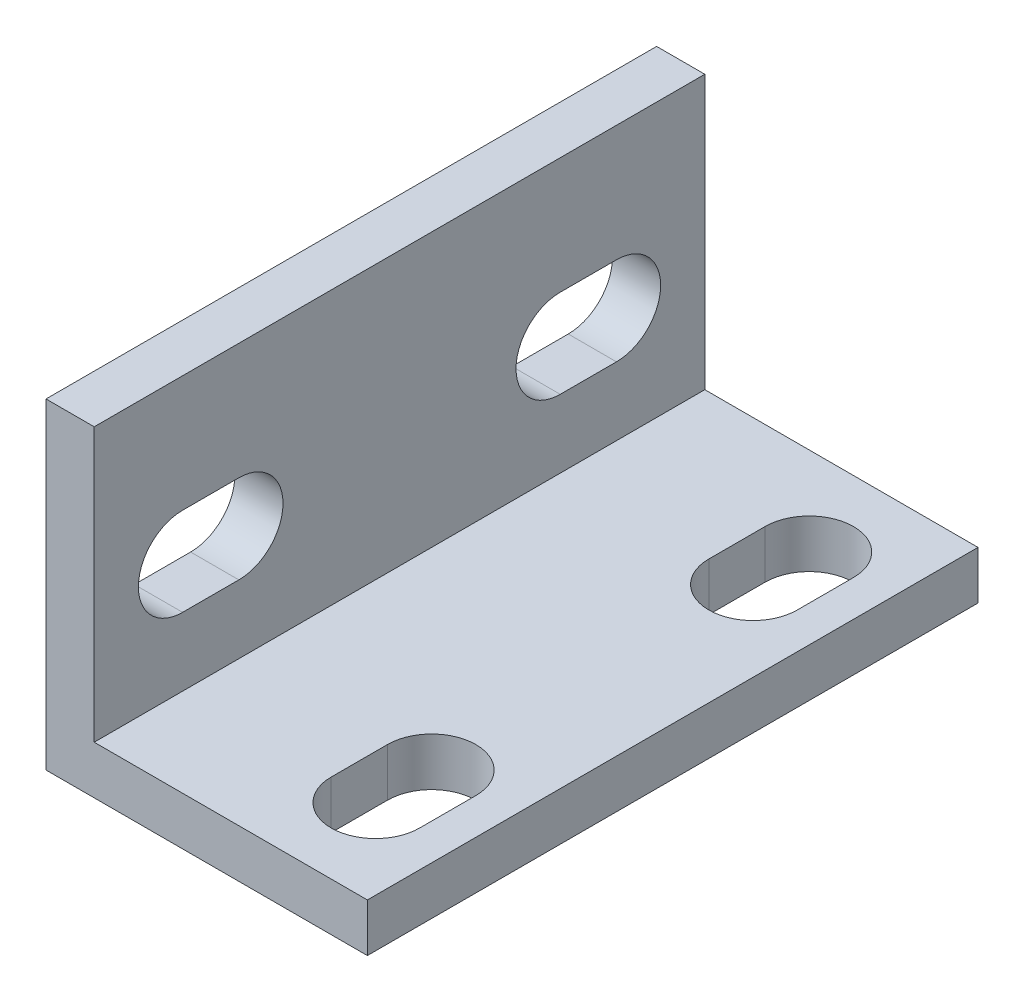
SolidWorks part; units mm, degrees
material "6061-T6 (SS)"
ref_plane "Front Plane" through (0, 0, 0) normal (0, 0, 1) x (1, 0, 0)
ref_plane "Top Plane" through (0, 0, 0) normal (0, 1, 0) x (1, 0, 0)
ref_plane "Right Plane" through (0, 0, 0) normal (1, 0, 0) x (0, 0, -1)
sketch "Sketch1" plane through (0, 0, 0) normal (0, 1, 0) x (1, 0, 0)
  line L1 (-10, 19) -> (10, 19)
  line L2 (-10, 19) -> (-10, -19)
  line L3 (-10, -19) -> (10, -19)
  line L4 (10, 19) -> (10, -19)
  line L5 (-10, 19) -> (10, -19) construction
  line L6 (-10, -19) -> (10, 19) construction
  point P0 (0, 0)
  dimension "D1" = 20
  dimension "D2" = 38
extrude "Boss-Extrude1" add sketch "Sketch1" along normal blind 20
sketch "Sketch2" plane through (0, 0, 19) normal (0, 0, 1) x (1, 0, 0)
  line L1 (10, 20) -> (-7, 20)
  line L2 (10, 20) -> (10, 3)
  line L3 (10, 3) -> (-7, 3)
  line L4 (-7, 20) -> (-7, 3)
  dimension "D1" = 17
  dimension "D2" = 17
extrude "Cut-Extrude1" cut sketch "Sketch2" against normal through all
sketch "Sketch3" plane through (0, 3, 0) normal (0, 1, 0) x (1, 0, 0)
  line L0 (5, -10) -> (5, -13.5) construction
  line L1 (7.75, -10) -> (7.75, -13.5)
  line L2 (2.25, -10) -> (2.25, -13.5)
  line L3 (10, 19) -> (10, -19) construction
  line L4 (-7, -19) -> (10, -19) construction
  line L5 (10, 0) -> (-10, 0) construction
  line L6 (-10, 19) -> (-10, -19) construction
  line L7 (5, 10) -> (5, 13.5) construction
  line L8 (7.75, 10) -> (7.75, 13.5)
  line L9 (2.25, 10) -> (2.25, 13.5)
  arc A0 (7.75, -10) -> (2.25, -10) centre (5, -10) ccw
  arc A1 (2.25, -13.5) -> (7.75, -13.5) centre (5, -13.5) ccw
  arc A2 (7.75, 10) -> (2.25, 10) centre (5, 10) cw
  arc A3 (2.25, 13.5) -> (7.75, 13.5) centre (5, 13.5) cw
  point P2 (5, -11.75)
  point P17 (0, 0)
  point P20 (5, 11.75)
  dimension "D1" = 2.75
  dimension "D2" = 3.5
  dimension "D3" = 5
  dimension "D4" = 5.5
extrude "Cut-Extrude2" cut sketch "Sketch3" against normal through all
sketch "Sketch4" plane through (-7, 0, 0) normal (1, 0, 0) x (0, 0, -1)
  line L0 (-13.5, 10) -> (-10, 10) construction
  line L1 (-13.5, 12.75) -> (-10, 12.75)
  line L2 (-13.5, 7.25) -> (-10, 7.25)
  line L3 (-19, 20) -> (-19, 3) construction
  line L4 (19, 3) -> (-19, 3) construction
  line L5 (0, 0) -> (0, 20) construction
  line L6 (-19, 0) -> (19, 0) construction
  line L7 (19, 20) -> (-19, 20) construction
  line L8 (13.5, 10) -> (10, 10) construction
  line L9 (13.5, 12.75) -> (10, 12.75)
  line L10 (13.5, 7.25) -> (10, 7.25)
  arc A0 (-13.5, 12.75) -> (-13.5, 7.25) centre (-13.5, 10) ccw
  arc A1 (-10, 7.25) -> (-10, 12.75) centre (-10, 10) ccw
  arc A2 (13.5, 12.75) -> (13.5, 7.25) centre (13.5, 10) cw
  arc A3 (10, 7.25) -> (10, 12.75) centre (10, 10) cw
  point P2 (-11.75, 10)
  point P19 (11.75, 10)
  dimension "D2" = 2.75
  dimension "D1" = 3.5
  dimension "D3" = 5.5
  dimension "D4" = 7
extrude "Cut-Extrude3" cut sketch "Sketch4" against normal through all
